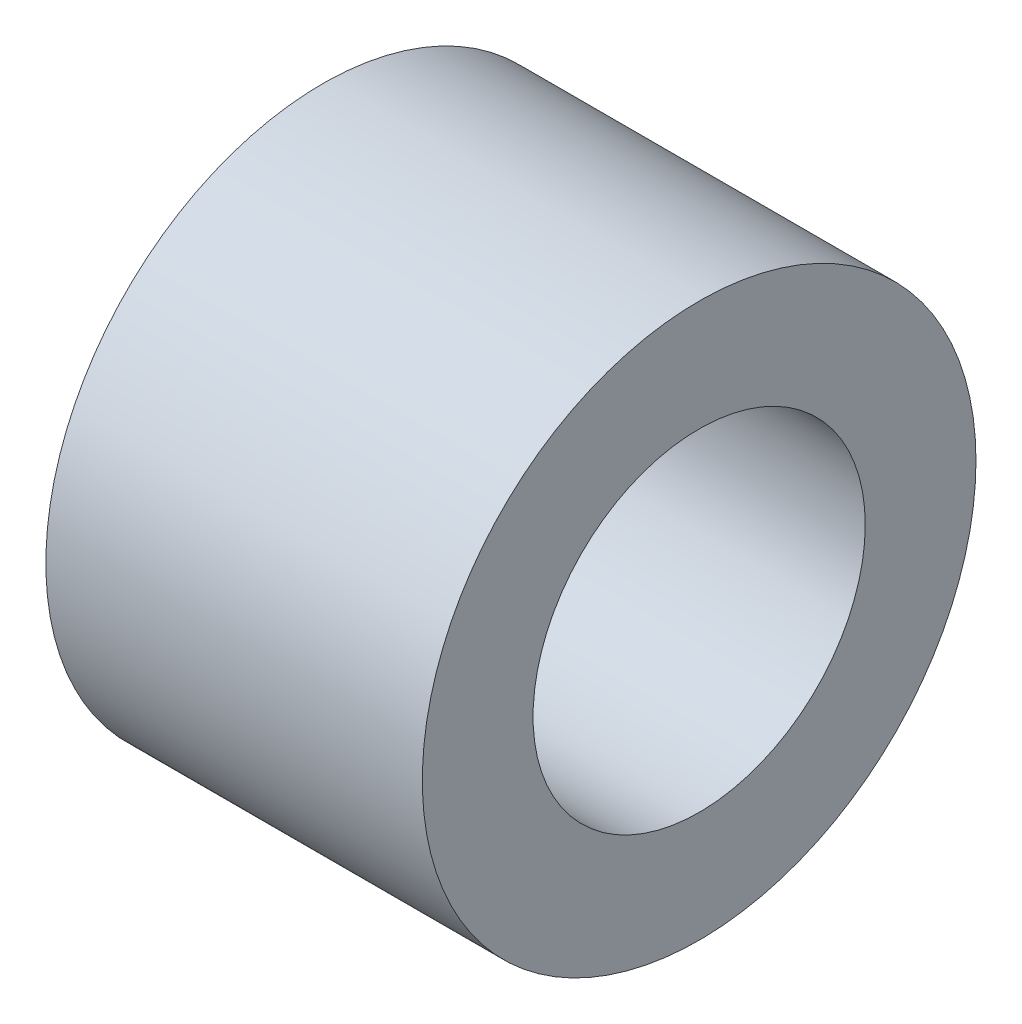
SolidWorks part; units mm, degrees
ref_plane "Front Plane" through (0, 0, 0) normal (0, 0, 1) x (1, 0, 0)
ref_plane "Top Plane" through (0, 0, 0) normal (0, 1, 0) x (1, 0, 0)
ref_plane "Right Plane" through (0, 0, 0) normal (1, 0, 0) x (0, 0, -1)
sketch "Sketch1" plane through (0, 0, 0) normal (1, 0, 0) x (0, 0, -1)
  circle A0 centre (0, 0) radius 2.5
  circle A1 centre (0, 0) radius 1.5
extrude "Boss-Extrude1" add sketch "Sketch1" along normal blind 3.4
